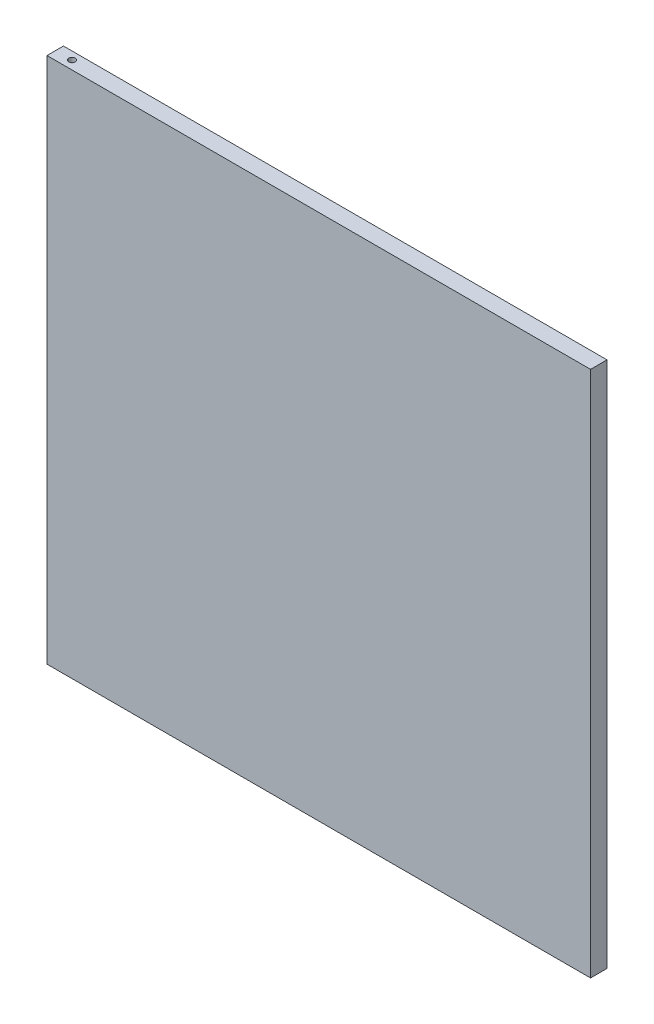
SolidWorks part; units mm, degrees
ref_plane "Płaszczyzna przednia" through (0, 0, 0) normal (0, 0, 1) x (1, 0, 0)
ref_plane "Płaszczyzna górna" through (0, 0, 0) normal (0, 1, 0) x (1, 0, 0)
ref_plane "Płaszczyzna prawa" through (0, 0, 0) normal (1, 0, 0) x (0, 0, -1)
sketch "Szkic1" plane through (0, 0, 0) normal (0, 0, 1) x (1, 0, 0)
  line L1 (0, 0) -> (825, 0)
  line L2 (0, 0) -> (0, 800)
  line L3 (0, 800) -> (825, 800)
  line L4 (825, 0) -> (825, 800)
  dimension "D1" = 800
  dimension "D2" = 825
extrude "Dodanie-wyciągnięcie1" add sketch "Szkic1" along normal blind 25
sketch "Szkic3" plane through (0, 0, 0) normal (0, 1, 0) x (1, 0, 0)
  circle A0 centre (25, -12) radius 5
  dimension "D1" = 10
  dimension "D2" = 13
  dimension "D3" = 25
ref_plane "Płaszczyzna1" through (0, 400, 0) normal (0, 1, 0) x (1, 0, 0)
extrude "Wytnij-wyciągnięcie1" cut sketch "Szkic3" along normal blind 40
mirror "Lustro1" about plane through (0, 400, 0) normal (0, 1, 0) of "Wytnij-wyciągnięcie1"
equation "\"Dodanie-wyciągnięcie1\" = IIF ( \"D2@Szkic1\" < 825 , \"suppressed\" , \"unsuppressed\" )"
